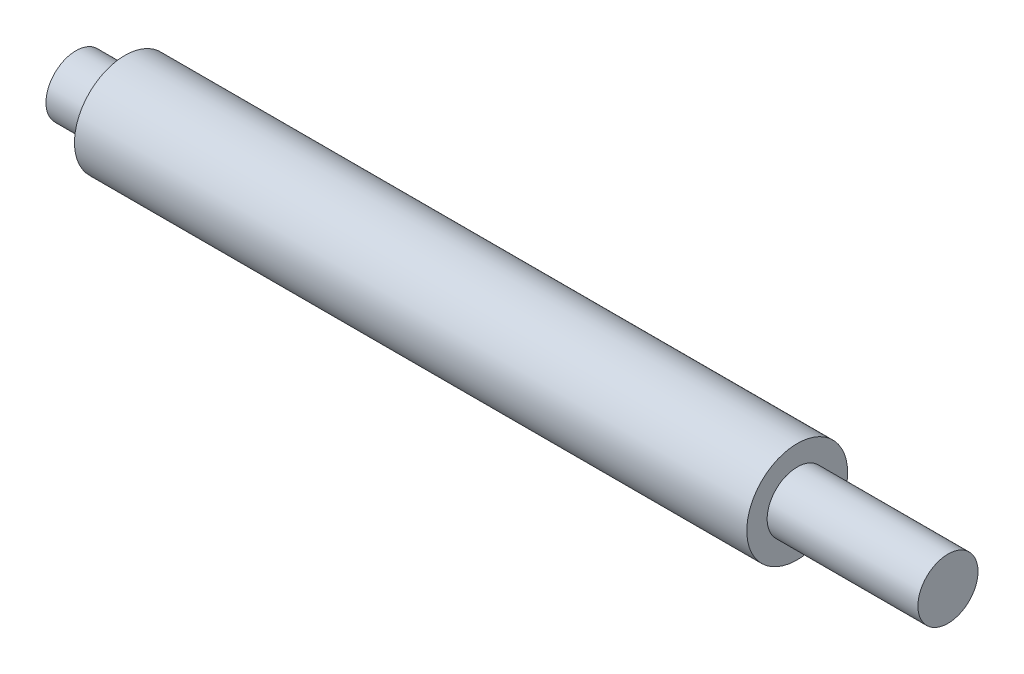
SolidWorks part; units mm, degrees
ref_plane "Front Plane" through (0, 0, 0) normal (1, 0, 0) x (0, 1, 0)
ref_plane "Top Plane" through (0, 0, 0) normal (0, 0, 1) x (0, 1, 0)
ref_plane "Right Plane" through (0, 0, 0) normal (0, 1, 0) x (-1, 0, 0)
sketch "Sketch1" plane through (0, 0, 0) normal (1, 0, 0) x (0, 1, 0)
  circle A0 centre (0, 0) radius 2.95
  dimension "D1" = 5.9
extrude "Boss-Extrude1" add sketch "Sketch1" along normal blind 4.8
sketch "Sketch2" plane through (4.8, 0, 0) normal (1, 0, 0) x (0, 1, 0)
  circle A0 centre (0, 0) radius 4.95
  dimension "D1" = 9.9
extrude "Boss-Extrude2" add sketch "Sketch2" along normal blind 66
sketch "Sketch3" plane through (70.8, 0, 0) normal (1, 0, 0) x (0, 1, 0)
  circle A0 centre (0, 0) radius 2.95
  dimension "D1" = 5.9
extrude "Boss-Extrude3" add sketch "Sketch3" along normal blind 14.8
